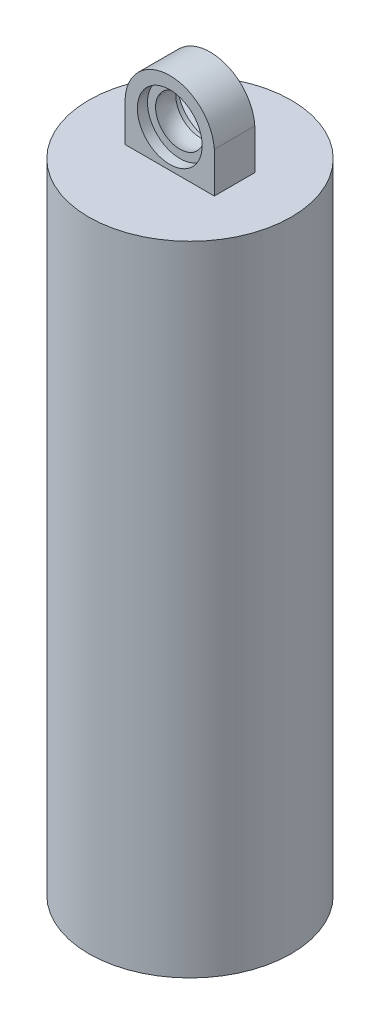
SolidWorks part; units mm, degrees
ref_plane "前视基准面" through (0, 0, 0) normal (0, 0, 1) x (1, 0, 0)
ref_plane "上视基准面" through (0, 0, 0) normal (0, 1, 0) x (1, 0, 0)
ref_plane "右视基准面" through (0, 0, 0) normal (1, 0, 0) x (0, 0, -1)
sketch "草图1" plane through (0, 0, 0) normal (0, 1, 0) x (1, 0, 0)
  circle A0 centre (0, 0) radius 25
  dimension "D1" = 50
extrude "凸台-拉伸1" add sketch "草图1" along normal blind 157.5
sketch "草图2" plane through (0, 0, 0) normal (0, -1, 0) x (1, 0, 0)
  circle A0 centre (0, 0) radius 12.5
  dimension "D1" = 25
extrude "凸台-拉伸2" add sketch "草图2" along normal blind 6
sketch "草图3" plane through (0, -6, 0) normal (0, -1, 0) x (1, 0, 0)
  circle A0 centre (0, 0) radius 6
  dimension "D1" = 12
extrude "切除-拉伸1" cut sketch "草图3" against normal blind 80
sketch "草图4" plane through (0, 0, 0) normal (0, 0, 1) x (1, 0, 0)
  line L0 (25, 157.5) -> (-25, 157.5) construction
  line L1 (-11, 157.5) -> (11, 157.5)
  line L2 (-11, 157.5) -> (-11, 167.5)
  line L4 (11, 157.5) -> (11, 167.5)
  line L5 (0, 193.283) -> (0, 138.3299) construction
  arc A0 (-11, 167.5) -> (11, 167.5) centre (0, 166.7613) cw
  circle A1 centre (0, 166.7613) radius 8
  dimension "D4" = 16
  dimension "D1" = 22
  dimension "D2" = 11
  dimension "D3" = 10
extrude "凸台-拉伸3" add sketch "草图4" against normal mid plane 10
sketch "草图5" plane through (0, 0, 0) normal (0, 0, 1) x (1, 0, 0)
  circle A0 centre (0, 166.7613) radius 8
extrude "凸台-拉伸4" add sketch "草图5" along normal mid plane 5
ref_plane "基准面4" through (0, 0, 4.5) normal (0, 0, 1) x (1, 0, 0)
sketch "草图7" plane through (0, 0, 2.5) normal (0, 0, 1) x (1, 0, 0)
  circle A0 centre (0, 166.7613) radius 6
  dimension "D1" = 12
sketch "草图8" plane through (0, 0, 4.5) normal (0, 0, 1) x (1, 0, 0)
  circle A0 centre (0, 166.7613) radius 4
  dimension "D1" = 8
loft "放样1" add profiles "草图8", "草图7"
mirror "镜向1" about plane through (0, 0, 0) normal (0, 0, 1) of "放样1"
sketch "草图9" plane through (0, 0, 4.5) normal (0, 0, 1) x (1, 0, 0)
  circle A0 centre (0, 166.7613) radius 2.5
  dimension "D1" = 5
extrude "切除-拉伸2" cut sketch "草图9" against normal blind 31
sketch "草图10" plane through (0, 0, 4.5) normal (0, 0, 1) x (1, 0, 0)
  circle A0 centre (0, 166.7613) radius 6
extrude "切除-拉伸3" cut sketch "草图10" against normal blind 17
sketch "草图11" plane through (0, 0, 0) normal (0, 0, 1) x (1, 0, 0)
  line L0 (0, 173.2613) -> (0, 160.2613)
  arc A0 (0, 160.2613) -> (0, 173.2613) centre (0, 166.7613) ccw
  dimension "D1" = 13
revolve "切除-旋转1" cut sketch "草图11" angle 360 about L0
